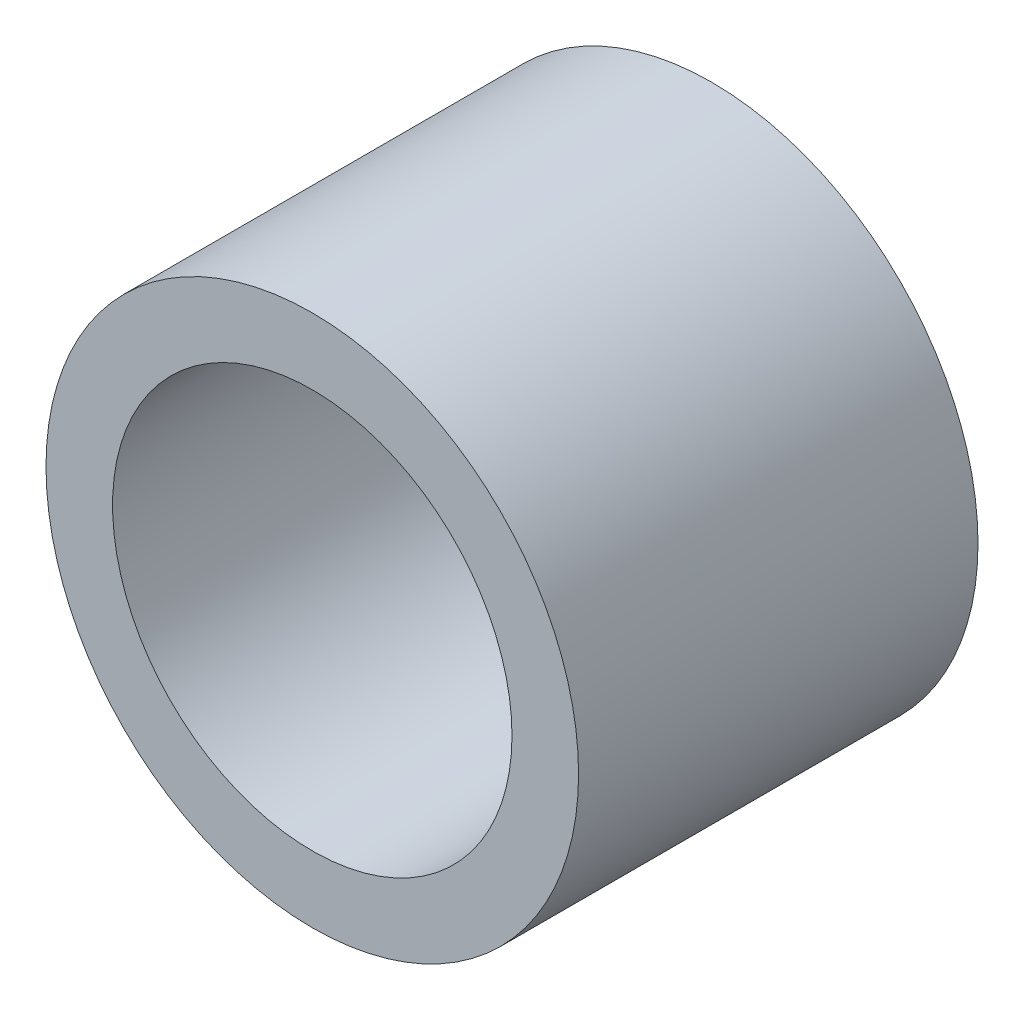
SolidWorks part; units mm, degrees
ref_plane "Front Plane" through (0, 0, 0) normal (0, 0, 1) x (1, 0, 0)
ref_plane "Top Plane" through (0, 0, 0) normal (0, 1, 0) x (1, 0, 0)
ref_plane "Right Plane" through (0, 0, 0) normal (1, 0, 0) x (0, 0, -1)
sketch "Sketch1" plane through (0, 0, 0) normal (1, 0, 0) x (0, 0, -1)
  line L0 (-23.2049, 0) -> (31.358, 0) construction
  line L2 (0, 12.7) -> (19.05, 12.7)
  line L3 (0, 12.7) -> (0, 9.525)
  line L4 (0, 9.525) -> (19.05, 9.525)
  line L5 (19.05, 12.7) -> (19.05, 9.525)
  point P7 (0, 0)
  dimension "D1" = 19.05
  dimension "D2" = 25.4
  dimension "D3" = 19.05
revolve "Revolve1" add sketch "Sketch1" angle 360 about L0
